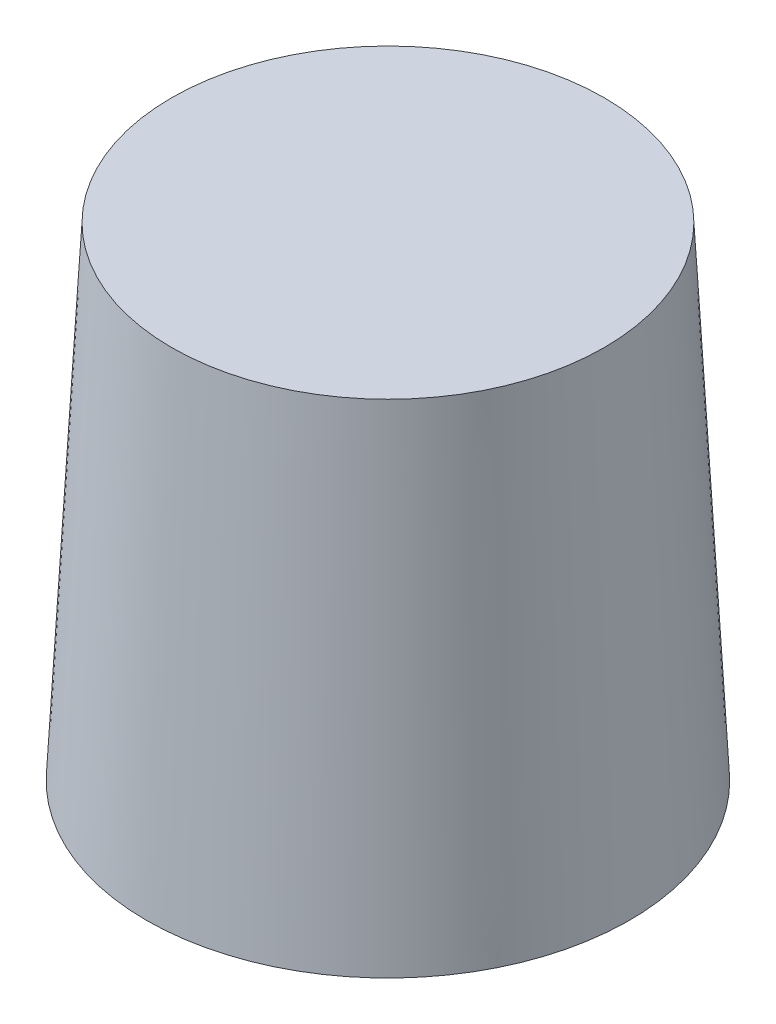
SolidWorks part; units mm, degrees
ref_plane "Спереди" through (0, 0, 0) normal (0, 0, 1) x (1, 0, 0)
ref_plane "Сверху" through (0, 0, 0) normal (0, 1, 0) x (1, 0, 0)
ref_plane "Справа" through (0, 0, 0) normal (1, 0, 0) x (0, 0, -1)
sketch "Sketch1" plane through (0, 0, 0) normal (0, 1, 0) x (1, 0, 0)
  circle A0 centre (0, 0) radius 10
  dimension "D1" = 20
extrude "Boss-Extrude1" add sketch "Sketch1" along normal blind 20 draft 3
sketch "Sketch2" plane through (0, 0, 0) normal (0, -1, 0) x (1, 0, 0)
  circle A0 centre (0, 0) radius 5
  dimension "D1" = 10
extrude "Cut-Extrude1" cut sketch "Sketch2" against normal blind 4
sketch "Sketch3" plane through (0, 4, 0) normal (0, -1, 0) x (1, 0, 0)
  line L0 (-1.7321, -2.571) -> (3.0483, -0.5639)
  line L1 (0.6581, -1.5674) -> (-1.2001, 2.8583) construction
  circle A0 centre (0, 0) radius 3.1 construction
  arc A1 (-1.7321, -2.571) -> (3.0483, -0.5639) centre (0, 0) cw
  dimension "D1" = 6.2
  dimension "D2" = 4.8
extrude "Cut-Extrude2" cut sketch "Sketch3" against normal blind 12
chamfer "Chamfer1" distance 1 angle 30 1 edges at (0, 0, -5)
